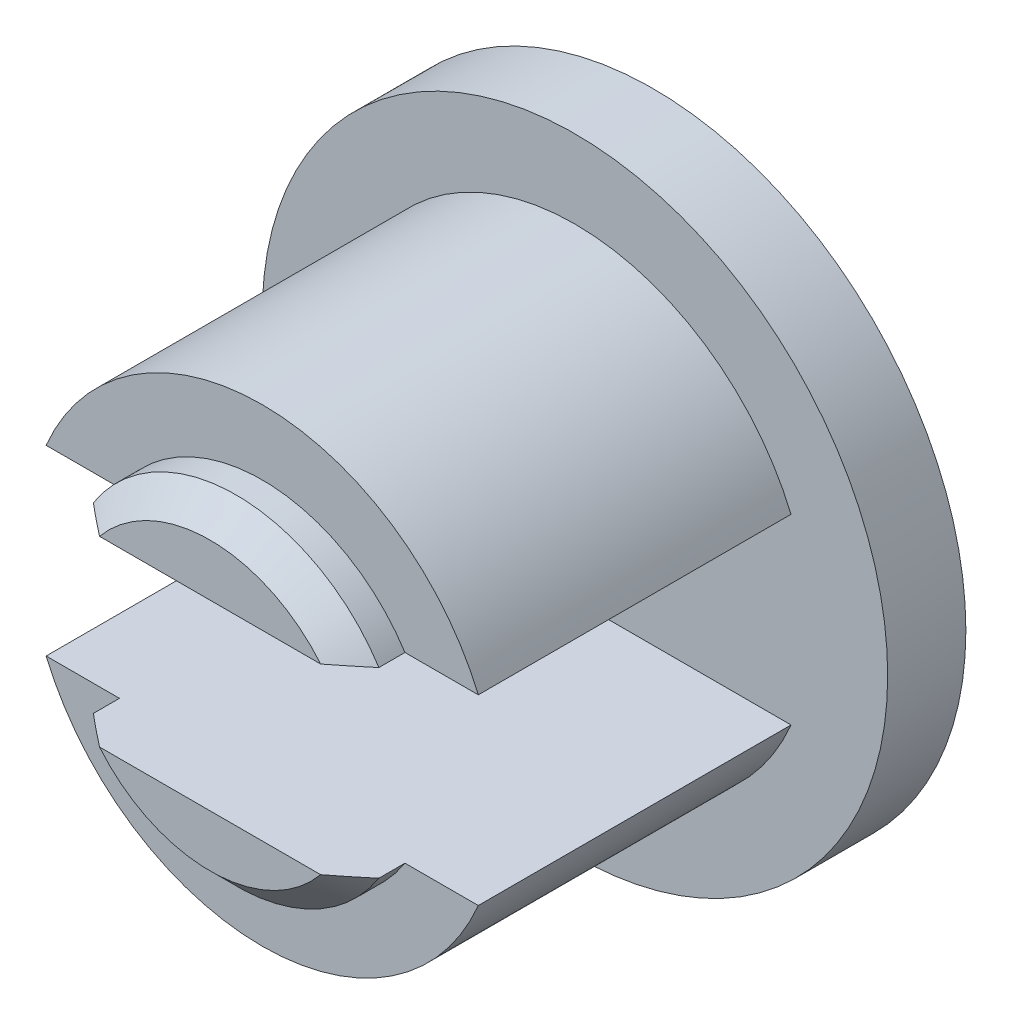
SolidWorks part; units mm, degrees
ref_plane "前视基准面" through (0, 0, 0) normal (0, 0, 1) x (1, 0, 0)
ref_plane "上视基准面" through (0, 0, 0) normal (0, 1, 0) x (1, 0, 0)
ref_plane "右视基准面" through (0, 0, 0) normal (1, 0, 0) x (0, 0, -1)
sketch "草图1" plane through (0, 0, 0) normal (0, 0, 1) x (1, 0, 0)
  circle A0 centre (0, 0) radius 2.5
  dimension "D1" = 5
extrude "凸台-拉伸1" add sketch "草图1" along normal blind 1.5
sketch "草图3" plane through (0, 0, 1.5) normal (0, 0, 1) x (1, 0, 0)
  circle A0 centre (0, 0) radius 6
  dimension "D1" = 12
extrude "凸台-拉伸2" add sketch "草图3" along normal blind 1.5
sketch "草图4" plane through (0, 0, 3) normal (0, 0, 1) x (1, 0, 0)
  circle A0 centre (0, 0) radius 4.5
  dimension "D1" = 9
extrude "凸台-拉伸3" add sketch "草图4" along normal blind 6
sketch "草图5" plane through (0, 0, 9) normal (0, 0, 1) x (1, 0, 0)
  circle A0 centre (0, 0) radius 3.25
  dimension "D1" = 6.5
extrude "凸台-拉伸4" add sketch "草图5" along normal blind 1
chamfer "倒角1" distance 0.5 angle 45 2 edges at (2.5, 0, 0) (3.25, 0, 10)
sketch "草图6" plane through (0, 0, 10) normal (0, 0, 1) x (1, 0, 0)
  line L1 (17.72, -1.75) -> (-17.72, -1.75)
  line L2 (17.72, -1.75) -> (17.72, 1.75)
  line L3 (17.72, 1.75) -> (-17.72, 1.75)
  line L4 (-17.72, -1.75) -> (-17.72, 1.75)
  line L5 (17.72, -1.75) -> (-17.72, 1.75) construction
  line L6 (17.72, 1.75) -> (-17.72, -1.75) construction
  point P0 (0, 0)
  dimension "D1" = 3.5
  dimension "D2" = 35.44
extrude "切除-拉伸1" cut sketch "草图6" against normal up to surface (7 mm away) up to face at (4.5, 0, 3)
